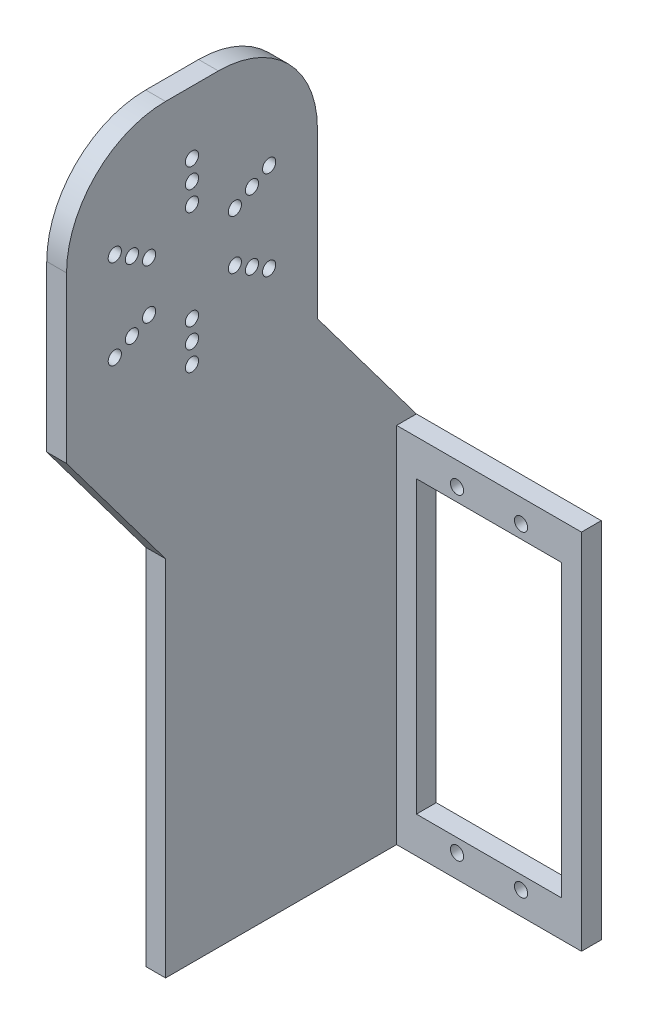
SolidWorks part; units mm, degrees
material "Polylactic Acid"
ref_plane "Front Plane" through (0, 0, 0) normal (0, 0, 1) x (1, 0, 0)
ref_plane "Top Plane" through (0, 0, 0) normal (0, 1, 0) x (1, 0, 0)
ref_plane "Right Plane" through (0, 0, 0) normal (1, 0, 0) x (0, 0, -1)
sketch "Sketch1" plane through (0, 0, 0) normal (0, 0, 1) x (1, 0, 0)
  line L0 (-4.85, -24) -> (4.85, -24) construction
  line L1 (-17, 27.5) -> (14, 27.5)
  line L2 (-17, 27.5) -> (-17, -27.5)
  line L3 (-17, -27.5) -> (14, -27.5)
  line L4 (14, 27.5) -> (14, -27.5)
  line L5 (-4.85, -24) -> (-4.85, 24) construction
  line L7 (-11, 22) -> (11, 22)
  line L8 (-11, 22) -> (-11, -22)
  line L9 (-11, -22) -> (11, -22)
  line L10 (11, 22) -> (11, -22)
  circle A0 centre (-4.85, -24) radius 1
  circle A1 centre (4.85, -24) radius 1
  circle A2 centre (4.85, 24) radius 1
  circle A3 centre (-4.85, 24) radius 1
  point P6 (0, -22)
  point P8 (-4.85, 0)
  point P12 (0, -24)
  point P22 (-11, 0)
  point P23 (11, 0)
  point P24 (14, 0)
  dimension "D5" = 2
  dimension "D3" = 9.7
  dimension "D4" = 48
  dimension "D6" = 44
  dimension "D7" = 22
  dimension "D8" = 55
  dimension "D9" = 6
  dimension "D10" = 3
  dimension "D1" = 2
  dimension "D2" = 2
extrude "Boss-Extrude1" add sketch "Sketch1" along normal blind 3
sketch "Sketch2" plane through (0, 0, 3) normal (0, 0, 1) x (1, 0, 0)
  line L0 (-17, -27.5) -> (14, -27.5) construction
  line L1 (-17, 27.5) -> (-14, 27.5)
  line L2 (-17, 27.5) -> (-17, -27.5)
  line L3 (-17, -27.5) -> (-14, -27.5)
  line L4 (-14, 27.5) -> (-14, -27.5)
  dimension "D1" = 3
extrude "Boss-Extrude2" add sketch "Sketch2" along normal blind 35
sketch "Sketch3" plane through (0, 27.5, 0) normal (0, 1, 0) x (1, 0, 0)
  line L0 (-14, -38) -> (-17, -38) construction
  line L1 (-17, 0) -> (-14, 0)
  line L2 (-17, 0) -> (-17, -53)
  line L3 (-17, -53) -> (-14, -53)
  line L4 (-14, 0) -> (-14, -53)
  dimension "D1" = 15
extrude "Boss-Extrude3" add sketch "Sketch3" along normal blind 20
sketch "Sketch4" plane through (-17, 0, 0) normal (-1, 0, 0) x (0, 0, 1)
  line L0 (53, 27.5) -> (38, 27.5)
  line L1 (38, 27.5) -> (53, 47.5)
  line L2 (53, 47.5) -> (53, 27.5)
  line L3 (0, 27.5) -> (0, 47.5)
  line L4 (0, 47.5) -> (15, 47.5)
  line L5 (0, 47.5) -> (53, 47.5) construction
  line L6 (15, 47.5) -> (0, 27.5)
extrude "Cut-Extrude1" cut sketch "Sketch4" against normal up to surface (3 mm away) up to face at (-14, 18.75, 23.5)
sketch "Sketch5" plane through (0, 47.5, 0) normal (0, 1, 0) x (1, 0, 0)
  line L1 (-17, -15) -> (-14, -15)
  line L2 (-17, -15) -> (-17, -53)
  line L3 (-17, -53) -> (-14, -53)
  line L4 (-14, -15) -> (-14, -53)
extrude "Boss-Extrude4" add sketch "Sketch5" along normal blind 40
sketch "Sketch6" plane through (-17, 0, 0) normal (-1, 0, 0) x (0, 0, 1)
  line L0 (34, 72) -> (34, 75) construction
  line L1 (34, 64.5) -> (34, 72) construction
  line L2 (15, 87.5) -> (53, 87.5) construction
  circle A0 centre (34, 72) radius 1
  circle A1 centre (34, 75) radius 1
  circle A2 centre (34, 78) radius 1
  circle A3 centre (45.6913, 71.25) radius 1
  circle A4 centre (43.0933, 69.75) radius 1
  circle A5 centre (40.4952, 68.25) radius 1
  circle A6 centre (45.6913, 57.75) radius 1
  circle A7 centre (43.0933, 59.25) radius 1
  circle A8 centre (40.4952, 60.75) radius 1
  circle A9 centre (34, 51) radius 1
  circle A10 centre (34, 54) radius 1
  circle A11 centre (34, 57) radius 1
  circle A12 centre (22.3087, 57.75) radius 1
  circle A13 centre (24.9067, 59.25) radius 1
  circle A14 centre (27.5048, 60.75) radius 1
  circle A15 centre (22.3087, 71.25) radius 1
  circle A16 centre (24.9067, 69.75) radius 1
  circle A17 centre (27.5048, 68.25) radius 1
  point P45 (34, 87.5)
  dimension "D3" = 2
  dimension "D2" = 3
  dimension "D5" = 7.5
  dimension "D6" = 23
  dimension "D1" = 3
  dimension "D4" = 6
extrude "Cut-Extrude2" cut sketch "Sketch6" against normal up to surface (3 mm away) up to face at (-14, 33.0556, 24.2222)
fillet "Fillet1" radius 15 2 edges at (-15.5, 87.5, 15) (-15.5, 87.5, 53)
